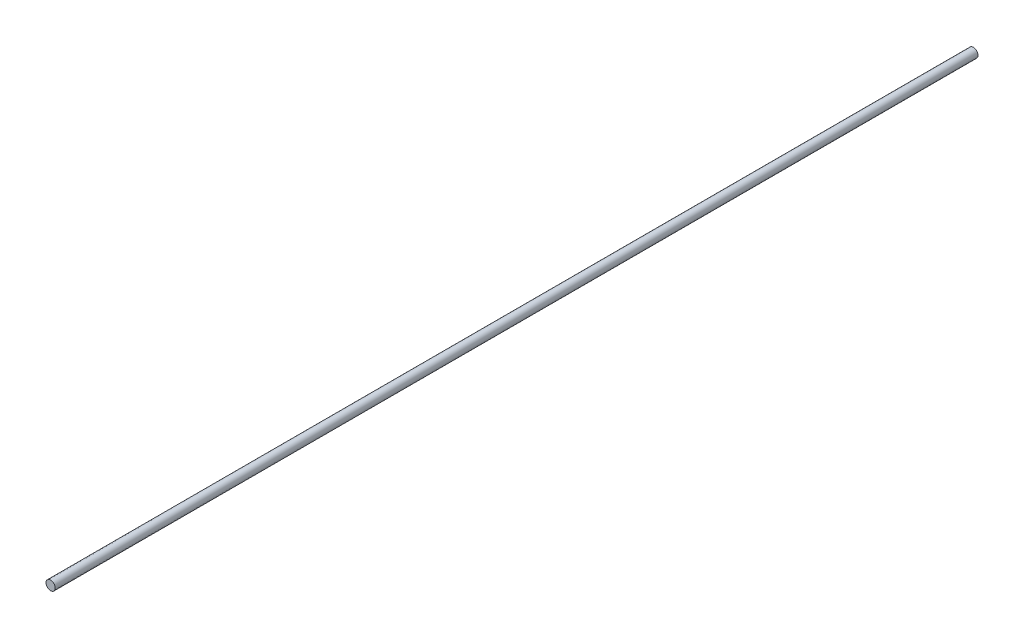
SolidWorks part; units mm, degrees
ref_plane "Front" through (0, 0, 0) normal (0, 0, 1) x (1, 0, 0)
ref_plane "Top" through (0, 0, 0) normal (0, 1, 0) x (1, 0, 0)
ref_plane "Right" through (0, 0, 0) normal (1, 0, 0) x (0, 0, -1)
sketch "Sketch1" plane through (0, 0, 0) normal (0, 0, 1) x (1, 0, 0)
  circle A0 centre (0, 0) radius 1
  dimension "dia" = 2
extrude "Extrude1" add sketch "Sketch1" along normal mid plane 200
sketch "Sketch2" plane through (0, 0, 0) normal (1, 0, 0) x (0, 0, -1)
  point P0 (-100, 1)
  point P1 (100, 1)
